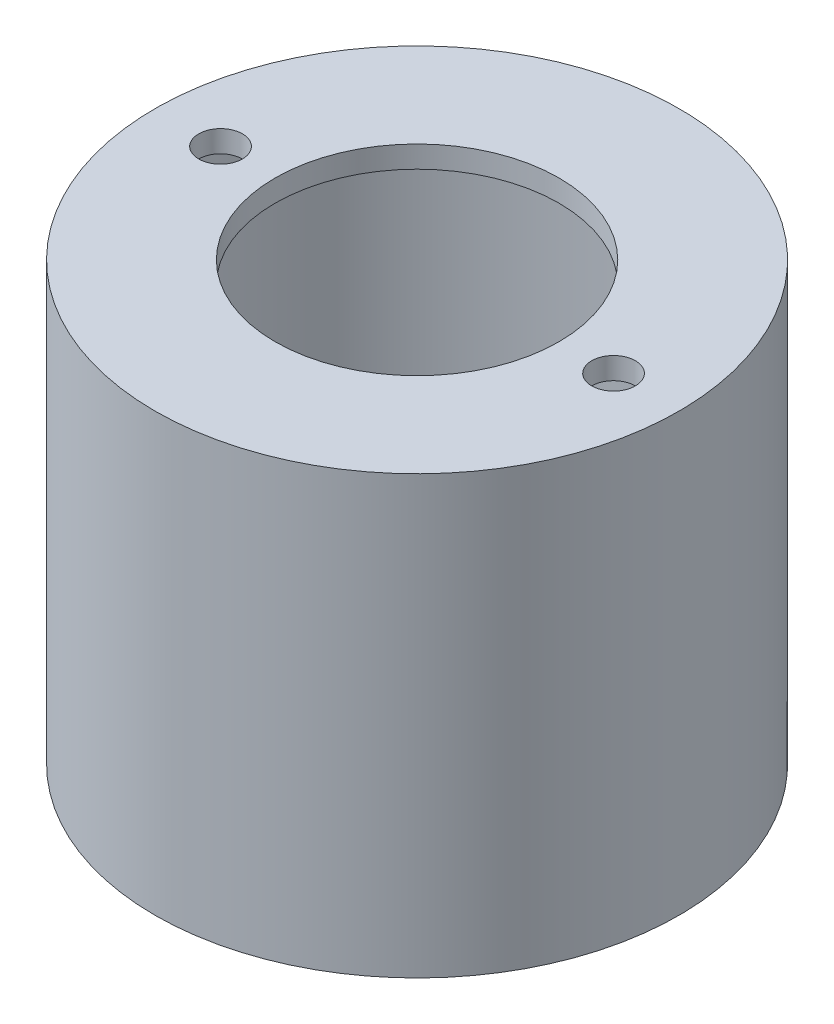
SolidWorks part; units mm, degrees
ref_plane "Front Plane" through (0, 0, 0) normal (0, 0, 1) x (1, 0, 0)
ref_plane "Top Plane" through (0, 0, 0) normal (0, 1, 0) x (1, 0, 0)
ref_plane "Right Plane" through (0, 0, 0) normal (1, 0, 0) x (0, 0, -1)
sketch "Sketch1" plane through (0, 0, 0) normal (0, 1, 0) x (1, 0, 0)
  circle A0 centre (0, 0) radius 60
  dimension "D1" = 120
extrude "Boss-Extrude1" add sketch "Sketch1" along normal blind 100
shell "Shell1" thickness 5
sketch "Sketch3" plane through (0, 100, 0) normal (0, 1, 0) x (1, 0, 0)
  circle A0 centre (0, 0) radius 32.5
  dimension "D1" = 65
extrude "Cut-Extrude1" cut sketch "Sketch3" against normal through all
sketch "Sketch4" plane through (0, 100, 0) normal (0, 1, 0) x (1, 0, 0)
  line L0 (0, -42.312) -> (0, 46.1969) construction
  circle A0 centre (45, 0) radius 5
  circle A1 centre (-45, 0) radius 5
  dimension "D1" = 10
  dimension "D2" = 45
extrude "Cut-Extrude2" cut sketch "Sketch4" against normal through all
